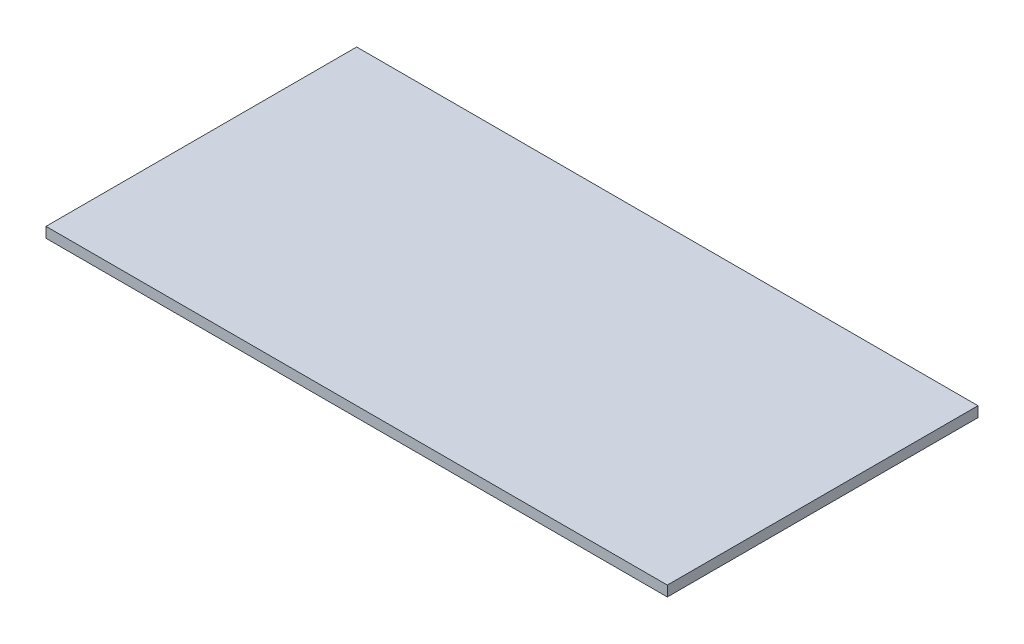
SolidWorks part; units mm, degrees
material "Sosna"
ref_plane "Płaszczyzna przednia" through (0, 0, 0) normal (0, 0, 1) x (1, 0, 0)
ref_plane "Płaszczyzna górna" through (0, 0, 0) normal (0, 1, 0) x (1, 0, 0)
ref_plane "Płaszczyzna prawa" through (0, 0, 0) normal (1, 0, 0) x (0, 0, -1)
sketch "Szkic1" plane through (0, 0, 0) normal (0, 1, 0) x (1, 0, 0)
  line L1 (0, 0) -> (600, 0)
  line L2 (0, 0) -> (0, 300)
  line L3 (0, 300) -> (600, 300)
  line L4 (600, 0) -> (600, 300)
  dimension "D1" = 300
  dimension "D2" = 600
extrude "Dodanie-wyciągnięcie1" add sketch "Szkic1" along normal blind 10
